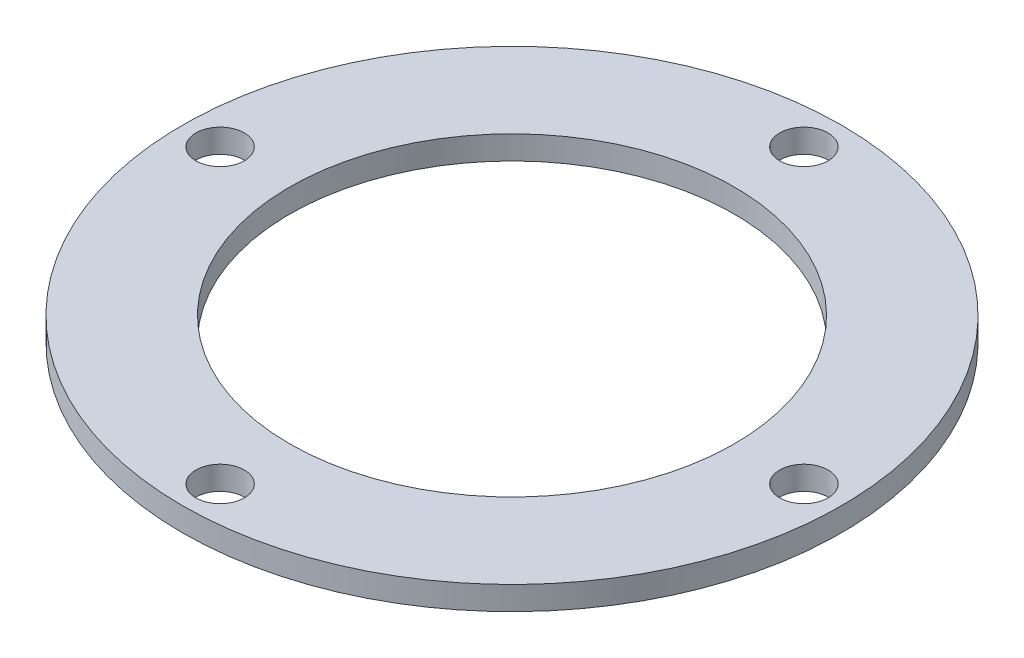
SolidWorks part; units mm, degrees
material "Brass"
ref_plane "Front Plane" through (0, 0, 0) normal (0, 0, 1) x (1, 0, 0)
ref_plane "Top Plane" through (0, 0, 0) normal (0, 1, 0) x (1, 0, 0)
ref_plane "Right Plane" through (0, 0, 0) normal (1, 0, 0) x (0, 0, -1)
sketch "Sketch1" plane through (0, 0, 0) normal (0, 1, 0) x (1, 0, 0)
  circle A0 centre (0, 0) radius 44.45
  circle A1 centre (0, 0) radius 30
  circle A2 centre (0, 39.37) radius 3.2639
  circle A3 centre (39.37, 0) radius 3.2639
  circle A4 centre (0, -39.37) radius 3.2639
  circle A5 centre (-39.37, 0) radius 3.2639
  point P15 (0, 0)
  dimension "D1" = 88.9
  dimension "D2" = 60
  dimension "D4" = 6.5278
  dimension "D3" = 39.37
  dimension "D5" = 4
extrude "Boss-Extrude1" add sketch "Sketch1" along normal blind 3.175
